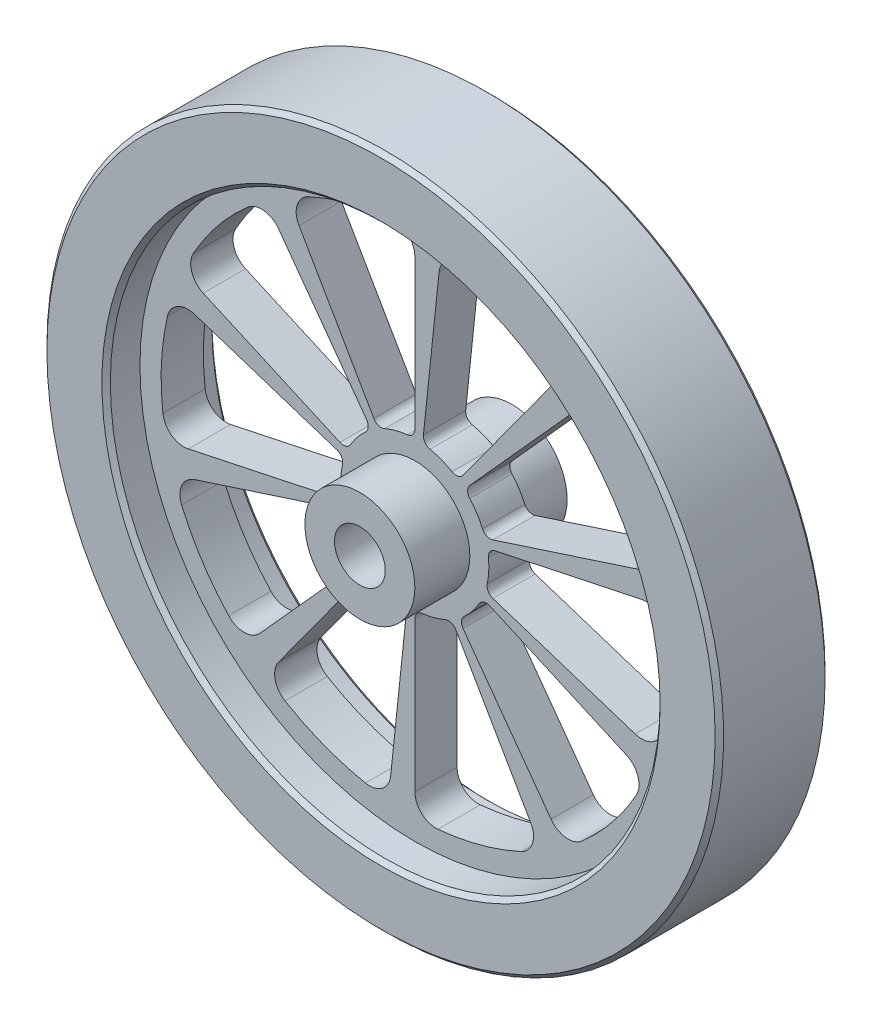
SolidWorks part; units mm, degrees
ref_plane "Front Plane" through (0, 0, 0) normal (0, 0, 1) x (1, 0, 0)
ref_plane "Top Plane" through (0, 0, 0) normal (0, 1, 0) x (1, 0, 0)
ref_plane "Right Plane" through (0, 0, 0) normal (1, 0, 0) x (0, 0, -1)
sketch "Sketch1" plane through (0, 0, 0) normal (0, 0, 1) x (1, 0, 0)
  circle A0 centre (0, 0) radius 80
  circle A1 centre (0, 0) radius 6
  dimension "D1" = 160
  dimension "D2" = 12
extrude "Boss-Extrude1" add sketch "Sketch1" along normal mid plane 26
sketch "Sketch2" plane through (0, 0, 13) normal (0, 0, 1) x (1, 0, 0)
  circle A0 centre (0, 0) radius 65
  dimension "D1" = 130
extrude "Cut-Extrude1" cut sketch "Sketch2" against normal blind 8
mirror "Mirror1" about plane through (0, 0, 0) normal (0, 0, 1) of "Cut-Extrude1"
sketch "Sketch3" plane through (0, 0, 0) normal (0, 0, 1) x (1, 0, 0)
  circle A0 centre (0, 0) radius 13
  circle A1 centre (0, 0) radius 65 construction
  circle A2 centre (0, 0) radius 80 construction
  circle A3 centre (0, 0) radius 65
  circle A4 centre (0, 0) radius 80
  circle A5 centre (0, 0) radius 6 construction
  circle A6 centre (0, 0) radius 6
  dimension "D1" = 26
extrude "Boss-Extrude2" add sketch "Sketch3" along normal mid plane 36 contours A0 A6
chamfer "Chamfer1" distance 1 angle 45 4 edges at (80, 0, -13) (65, 0, -13) (80, 0, 13) (65, 0, 13)
sketch "Sketch7" plane through (0, 0, 5) normal (0, 0, 1) x (1, 0, 0)
  line L0 (0, 17.5) -> (0, 60) construction
  line L1 (-8.75, 15.1554) -> (-30, 51.9615) construction
  line L2 (0, 54.7723) -> (0, 19.3972)
  line L3 (-27.3861, 47.4342) -> (-9.6986, 16.7984)
  arc A0 (-5.4545, 59.7516) -> (-25.152, 54.4736) centre (0, 0) ccw
  arc A1 (-1.7949, 17.4077) -> (-7.1495, 15.973) centre (0, 0) ccw
  arc A2 (0, 54.7723) -> (-5.4545, 59.7516) centre (-5, 54.7723) ccw
  arc A3 (-27.3861, 47.4342) -> (-25.152, 54.4736) centre (-23.056, 49.9342) cw
  arc A4 (-1.7949, 17.4077) -> (0, 19.3972) centre (-2, 19.3972) ccw
  arc A5 (-7.1495, 15.973) -> (-9.6986, 16.7984) centre (-7.9665, 17.7984) cw
  dimension "D1" = 120
  dimension "D2" = 35
  dimension "D4" = 5
  dimension "D5" = 2
  dimension "D3" = 30
extrude "Cut-Extrude2" cut sketch "Sketch7" against normal through all contours L2 A0 L3
pattern_circular "CirPattern1" count 10 over 360 about axis through (0, 0, 0) along (0, 0, 1) of "Cut-Extrude2"
